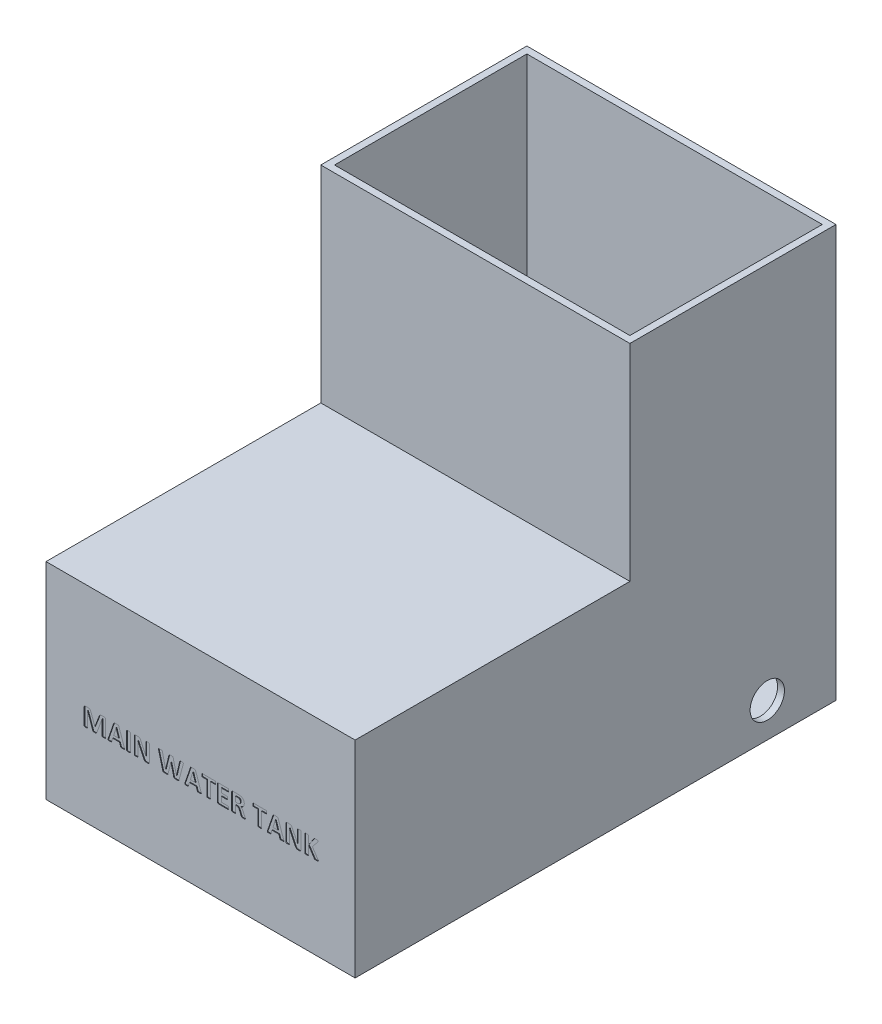
SolidWorks part; units mm, degrees
other "Markup1"
sketch "Sketch4" plane through (225, 600, 200) normal (0.2795, 0.2417, 0.9292) x (0.9251, 0.1914, -0.328)
sketch "Sketch7" plane through (225, 600, 200) normal (0.2795, 0.2417, 0.9292) x (0.9251, 0.1914, -0.328)
sketch "Sketch8" plane through (225, 600, 200) normal (0.2795, 0.2417, 0.9292) x (0.9251, 0.1914, -0.328)
material "ABS PC"
ref_plane "Front Plane" through (0, 0, 0) normal (0, 0, 1) x (1, 0, 0)
ref_plane "Top Plane" through (0, 0, 0) normal (0, 1, 0) x (1, 0, 0)
ref_plane "Right Plane" through (0, 0, 0) normal (1, 0, 0) x (0, 0, -1)
sketch "Sketch1" plane through (0, 0, 0) normal (0, 1, 0) x (1, 0, 0)
  line L1 (-225, 200) -> (225, 200)
  line L2 (-225, 200) -> (-225, -200)
  line L3 (-225, -200) -> (225, -200)
  line L4 (225, 200) -> (225, -200)
  line L5 (-225, 200) -> (225, -200) construction
  line L6 (-225, -200) -> (225, 200) construction
  point P0 (0, 0)
  dimension "D1" = 450
  dimension "D2" = 400
extrude "Boss-Extrude1" add sketch "Sketch1" along normal blind 300
sketch "Sketch3" plane through (0, 0, 0) normal (0, 1, 0) x (1, 0, 0)
  line L0 (225, -200) -> (225, 200) construction
  line L1 (-225, 200) -> (225, 200)
  line L2 (-225, 200) -> (-225, 500)
  line L3 (-225, 500) -> (225, 500)
  line L4 (225, 200) -> (225, 500)
  dimension "D1" = 300
extrude "Boss-Extrude2" add sketch "Sketch3" along normal blind 600
shell "Shell3" thickness 10
sketch "Sketch5" plane through (225, 0, 0) normal (1, 0, 0) x (0, 0, -1)
  line L0 (500, 600) -> (500, 0) construction
  line L1 (-200, 0) -> (500, 0) construction
  circle A0 centre (400, 50) radius 25
  dimension "D1" = 50
  dimension "D2" = 100
  dimension "D3" = 50
extrude "Cut-Extrude1" cut sketch "Sketch5" against normal up to next
sketch "Sketch6" plane through (0, 0, 200) normal (0, 0, 1) x (1, 0, 0)
  line L0 (-225, 120) -> (225, 120) construction
  line L1 (-225, 300) -> (-225, 0) construction
  line L2 (225, 300) -> (225, 0) construction
  line L3 (-225, 0) -> (225, 0) construction
  text T0 "MAIN WATER TANK" font "Calibri" height in points 100
  dimension "D1" = 120
extrude "Cut-Extrude2" cut sketch "Sketch6" against normal blind 1
